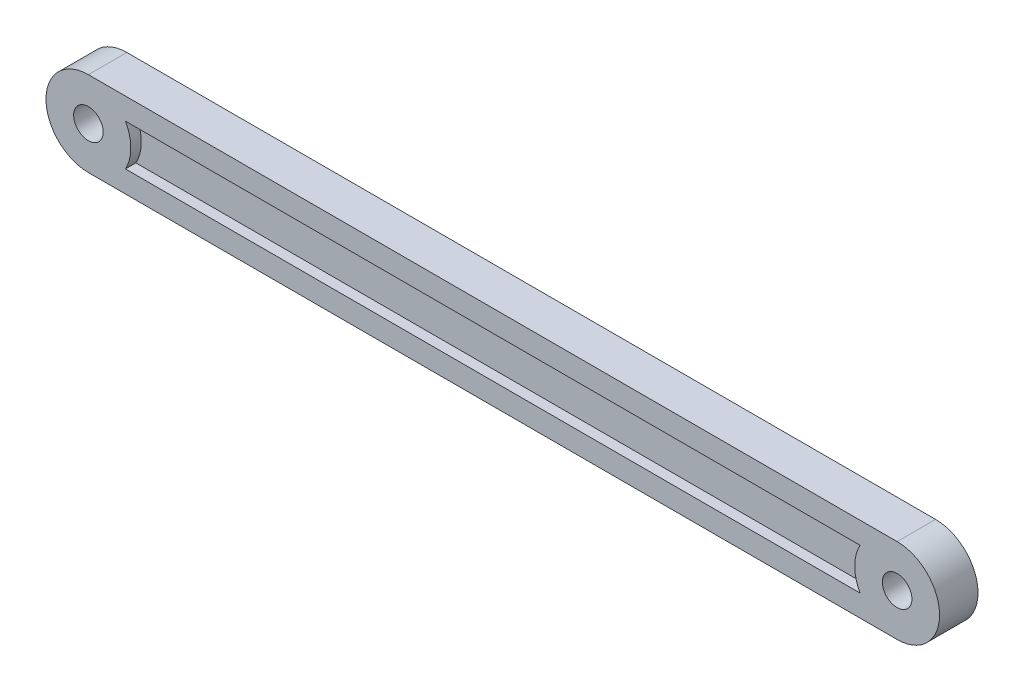
SolidWorks part; units mm, degrees
ref_plane "Front Plane" through (0, 0, 0) normal (0, 0, 1) x (1, 0, 0)
ref_plane "Top Plane" through (0, 0, 0) normal (0, 1, 0) x (1, 0, 0)
ref_plane "Right Plane" through (0, 0, 0) normal (1, 0, 0) x (0, 0, -1)
sketch "Sketch1" plane through (0, 0, 0) normal (0, 0, 1) x (1, 0, 0)
  line L0 (41, 0) -> (-41, 0) construction
  line L1 (41, -4.3) -> (-41, -4.3)
  line L2 (41, 4.3) -> (-41, 4.3)
  arc A0 (41, -4.3) -> (41, 4.3) centre (41, 0) ccw
  arc A1 (-41, 4.3) -> (-41, -4.3) centre (-41, 0) ccw
  circle A2 centre (-41, 0) radius 1.5
  circle A3 centre (41, 0) radius 1.5
  point P2 (0, 0)
  dimension "D3" = 3
  dimension "D1" = 8.6
  dimension "D2" = 82
extrude "Boss-Extrude1" add sketch "Sketch1" along normal mid plane 3.9
sketch "Sketch2" plane through (0, 0, 1.95) normal (0, 0, 1) x (1, 0, 0)
  line L0 (41, 2.1) -> (-41, 2.1)
  line L1 (-41, -2.1) -> (41, -2.1)
  line L2 (41, 4.3) -> (-41, 4.3)
  line L3 (-41, -4.3) -> (41, -4.3)
  line L4 (41, 4.3) -> (-41, 4.3)
  line L5 (-41, -4.3) -> (41, -4.3)
  arc A2 (41, -4.3) -> (41, 4.3) centre (41, 0) ccw
  arc A3 (-41, 4.3) -> (-41, -4.3) centre (-41, 0) ccw
  arc A4 (41, -4.3) -> (41, 4.3) centre (41, 0) ccw
  arc A5 (-41, 4.3) -> (-41, -4.3) centre (-41, 0) ccw
  circle A8 centre (-41, 0) radius 4.3
  circle A9 centre (41, 0) radius 4.3
  arc A10 (41, -2.1) -> (41, 2.1) centre (41, 0) ccw
  arc A11 (-41, 2.1) -> (-41, -2.1) centre (-41, 0) ccw
  dimension "D1" = 0
  dimension "D2" = 2.2
extrude "Cut-Extrude1" cut sketch "Sketch2" against normal blind 1.06 contours A9 L0 A8 L1
mirror "Mirror1" about plane through (0, 0, 0) normal (0, 0, 1) of "Cut-Extrude1"
